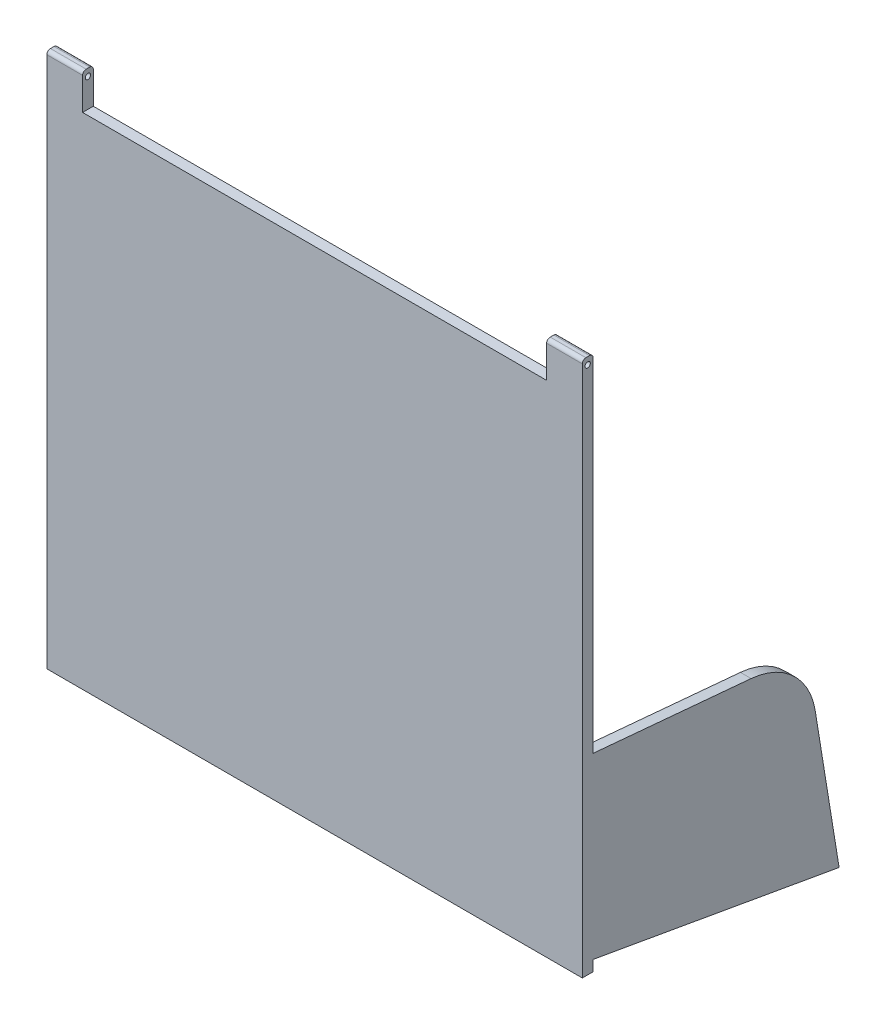
SolidWorks part; units mm, degrees
ref_plane "Plan de face" through (0, 0, 0) normal (0, 0, 1) x (1, 0, 0)
ref_plane "Plan de dessus" through (0, 0, 0) normal (0, 1, 0) x (1, 0, 0)
ref_plane "Plan de droite" through (0, 0, 0) normal (1, 0, 0) x (0, 0, -1)
sketch "Esquisse1" plane through (0, 0, 0) normal (0, 0, 1) x (1, 0, 0)
  line L1 (0, 0) -> (150, 0)
  line L2 (0, 0) -> (0, 150)
  line L3 (0, 150) -> (150, 150)
  line L4 (150, 0) -> (150, 150)
  dimension "D1" = 150
extrude "Boss.-Extru.1" add sketch "Esquisse1" along normal blind 3
sketch "Esquisse3" plane through (0, 0, 3) normal (0, 0, 1) x (1, 0, 0)
  line L0 (150, 150) -> (0, 150) construction
  line L1 (10, 150) -> (140, 150)
  line L2 (10, 150) -> (10, 140)
  line L3 (10, 140) -> (140, 140)
  line L4 (140, 150) -> (140, 140)
  line L5 (0, 150) -> (0, 0) construction
  line L6 (150, 0) -> (150, 150) construction
  dimension "D1" = 10
  dimension "D2" = 10
  dimension "D3" = 10
extrude "Enlèv. mat.-Extru.1" cut sketch "Esquisse3" against normal blind 3
sketch "Esquisse4" plane through (10, 0, 0) normal (1, 0, 0) x (0, 0, -1)
  line L0 (-1.5, 150) -> (-1.5, 140) construction
  line L1 (0, 150) -> (-3, 150) construction
  line L2 (0, 140) -> (-3, 140) construction
  circle A0 centre (-1.5, 148) radius 0.75
  dimension "D1" = 2
extrude "Enlèv. mat.-Extru.2" cut sketch "Esquisse4" against normal blind 200 and the other way blind 153
fillet "Congé1" radius 1 4 edges at (5, 150, 0) (5, 150, 3) (145, 150, 3) (145, 150, 0)
sketch "Esquisse8" plane through (150, 0, 0) normal (1, 0, 0) x (0, 0, -1)
  line L0 (0, 0) -> (0, 149) construction
  line L1 (-3, 0) -> (0, 0) construction
  line L2 (0, 3) -> (68.9365, -9.1554)
  line L3 (0, 53) -> (59.7575, 47.611)
  line L4 (59.7575, 47.611) -> (68.9365, -9.1554)
  line L5 (0, 53) -> (0, 3)
  point P0 (0, 3)
  point P5 (0, 53)
  dimension "D1" = 3
  dimension "D2" = 50
  dimension "D3" = 100
  dimension "D4" = 70
  dimension "D5" = 60
extrude "Boss.-Extru.5" add sketch "Esquisse8" against normal blind 3
sketch "Esquisse9" plane through (0, 0, 0) normal (-1, 0, 0) x (0, 0, 1)
  line L0 (0, 53) -> (-59.7575, 47.611)
  line L1 (-59.7575, 47.611) -> (-68.9365, -9.1554)
  line L2 (-68.9365, -9.1554) -> (0, 3)
  line L3 (0, 3) -> (0, 53)
extrude "Boss.-Extru.6" add sketch "Esquisse9" against normal blind 3
fillet "Congé4" radius 20 2 edges at (1.5, 47.611, -59.7575) (148.5, 47.611, -59.7575)
